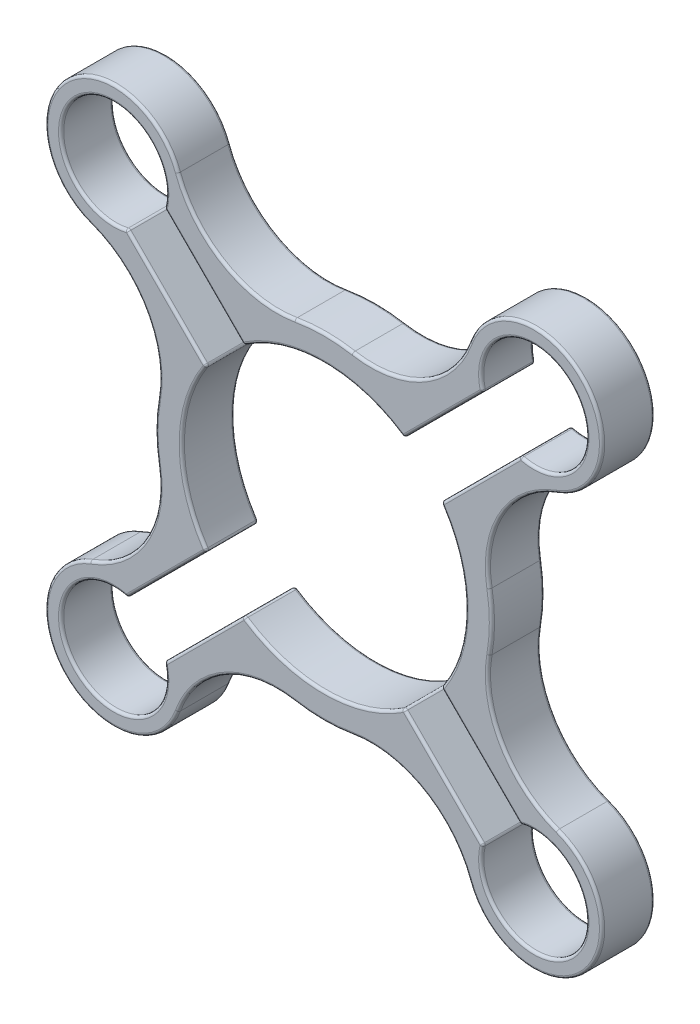
SolidWorks part; units mm, degrees
ref_plane "Front Plane" through (0, 0, 0) normal (0, 0, 1) x (1, 0, 0)
ref_plane "Top Plane" through (0, 0, 0) normal (0, 1, 0) x (1, 0, 0)
ref_plane "Right Plane" through (0, 0, 0) normal (1, 0, 0) x (0, 0, -1)
sketch "Sketch1" plane through (0, 0, 0) normal (0, 0, 1) x (1, 0, 0)
  line L0 (0, 0) -> (0, 55673.7554) construction
  line L1 (0, 0) -> (55673.7554, 0) construction
  line L2 (0, 0) -> (39.9515, 39.9515) construction
  line L3 (15.2261, 22.2972) -> (30.2923, 37.3633)
  line L4 (22.2972, 15.2261) -> (37.3633, 30.2923)
  line L5 (22.2972, -15.2261) -> (37.3633, -30.2923)
  line L6 (15.2261, -22.2972) -> (30.2923, -37.3633)
  line L7 (-15.2261, -22.2972) -> (-30.2923, -37.3633)
  line L8 (-22.2972, -15.2261) -> (-37.3633, -30.2923)
  line L9 (-22.2972, 15.2261) -> (-37.3633, 30.2923)
  line L10 (-15.2261, 22.2972) -> (-30.2923, 37.3633)
  arc A11 (15.2261, 22.2972) -> (-15.2261, 22.2972) centre (0, 0) ccw
  arc A12 (5.4999, 31.5238) -> (-5.4999, 31.5238) centre (0, 0) ccw
  circle A13 centre (0, 0) radius 56.5 construction
  arc A14 (37.3633, 30.2923) -> (30.2923, 37.3633) centre (39.9515, 39.9515) ccw
  arc A15 (44.3931, 27.7338) -> (27.7338, 44.3931) centre (39.9515, 39.9515) ccw
  arc A16 (44.3931, 27.7338) -> (31.5238, 5.4999) centre (51.2262, 8.9373) ccw
  arc A17 (27.7338, 44.3931) -> (5.4999, 31.5238) centre (8.9373, 51.2262) cw
  arc A18 (27.7338, -44.3931) -> (44.3931, -27.7338) centre (39.9515, -39.9515) ccw
  arc A19 (30.2923, -37.3633) -> (37.3633, -30.2923) centre (39.9515, -39.9515) ccw
  arc A20 (44.3931, -27.7338) -> (31.5238, -5.4999) centre (51.2262, -8.9373) cw
  arc A21 (27.7338, -44.3931) -> (5.4999, -31.5238) centre (8.9373, -51.2262) ccw
  arc A22 (-44.3931, -27.7338) -> (-27.7338, -44.3931) centre (-39.9515, -39.9515) ccw
  arc A23 (-37.3633, -30.2923) -> (-30.2923, -37.3633) centre (-39.9515, -39.9515) ccw
  arc A24 (-27.7338, -44.3931) -> (-5.4999, -31.5238) centre (-8.9373, -51.2262) cw
  arc A25 (-44.3931, -27.7338) -> (-31.5238, -5.4999) centre (-51.2262, -8.9373) ccw
  arc A26 (-27.7338, 44.3931) -> (-44.3931, 27.7338) centre (-39.9515, 39.9515) ccw
  arc A27 (-30.2923, 37.3633) -> (-37.3633, 30.2923) centre (-39.9515, 39.9515) ccw
  arc A28 (-44.3931, 27.7338) -> (-31.5238, 5.4999) centre (-51.2262, 8.9373) cw
  arc A29 (-27.7338, 44.3931) -> (-5.4999, 31.5238) centre (-8.9373, 51.2262) ccw
  arc A30 (-31.5238, 5.4999) -> (-31.5238, -5.4999) centre (0, 0) ccw
  arc A31 (-22.2972, 15.2261) -> (-22.2972, -15.2261) centre (0, 0) ccw
  arc A32 (-5.4999, -31.5238) -> (5.4999, -31.5238) centre (0, 0) ccw
  arc A33 (-15.2261, -22.2972) -> (15.2261, -22.2972) centre (0, 0) ccw
  arc A34 (31.5238, -5.4999) -> (31.5238, 5.4999) centre (0, 0) ccw
  arc A35 (22.2972, -15.2261) -> (22.2972, 15.2261) centre (0, 0) ccw
  point P6 (0, 0)
  point P54 (0, 0)
  dimension "D1" = 64
  dimension "D2" = 54
  dimension "D3" = 113
  dimension "D4" = 20
  dimension "D5" = 26
  dimension "D9" = 10
  dimension "D7" = 20
  dimension "D8" = 20
  dimension "D6" = 45
extrude "Boss-Extrude1" add sketch "Sketch1" along normal mid plane 10
fillet "Fillet1" radius 0.5 80 edges at (32, 0, 5) (33.9167, -18.9563, 5) (49.1439, -49.1439, 5) (18.9563, -33.9167, 5) (0, -32, 5) (-18.9563, -33.9167, 5) (-49.1439, -49.1439, 5) (-33.9167, -18.9563, 5) (-32, 0, 5) (-33.9167, 18.9563, 5) (-49.1439, 49.1439, 5) (-18.9563, 33.9167, 5) (0, 32, 5) (18.9563, 33.9167, 5) (49.1439, 49.1439, 5) (33.9167, 18.9563, 5) (32, 0, -5) (33.9167, -18.9563, -5) (49.1439, -49.1439, -5) (18.9563, -33.9167, -5) (0, -32, -5) (-18.9563, -33.9167, -5) (-49.1439, -49.1439, -5) (-33.9167, -18.9563, -5) (-32, 0, -5) (-33.9167, 18.9563, -5) (-49.1439, 49.1439, -5) (-18.9563, 33.9167, -5) (0, 32, -5) (18.9563, 33.9167, -5) (49.1439, 49.1439, -5) (33.9167, 18.9563, -5) (-15.2261, 22.2972, 0) (-30.2923, 37.3633, 0) (-37.3633, 30.2923, 0) (-22.2972, 15.2261, 0) (-22.2972, -15.2261, 0) (-37.3633, -30.2923, 0) (-30.2923, -37.3633, 0) (-15.2261, -22.2972, 0) (15.2261, -22.2972, 0) (30.2923, -37.3633, 0) (37.3633, -30.2923, 0) (22.2972, -15.2261, 0) (22.2972, 15.2261, 0) (37.3633, 30.2923, 0) (30.2923, 37.3633, 0) (15.2261, 22.2972, 0) (22.7592, 29.8303, 5) (47.0226, 47.0226, 5) (29.8303, 22.7592, 5) (27, 0, 5) (29.8303, -22.7592, 5) (47.0226, -47.0226, 5) (22.7592, -29.8303, 5) (0, -27, 5) (-22.7592, -29.8303, 5) (-47.0226, -47.0226, 5) (-29.8303, -22.7592, 5) (-27, 0, 5) (-29.8303, 22.7592, 5) (-47.0226, 47.0226, 5) (-22.7592, 29.8303, 5) (0, 27, 5) (22.7592, 29.8303, -5) (47.0226, 47.0226, -5) (29.8303, 22.7592, -5) (27, 0, -5) (29.8303, -22.7592, -5) (47.0226, -47.0226, -5) (22.7592, -29.8303, -5) (0, -27, -5) (-22.7592, -29.8303, -5) (-47.0226, -47.0226, -5) (-29.8303, -22.7592, -5) (-27, 0, -5) (-29.8303, 22.7592, -5) (-47.0226, 47.0226, -5) (-22.7592, 29.8303, -5) (0, 27, -5)
